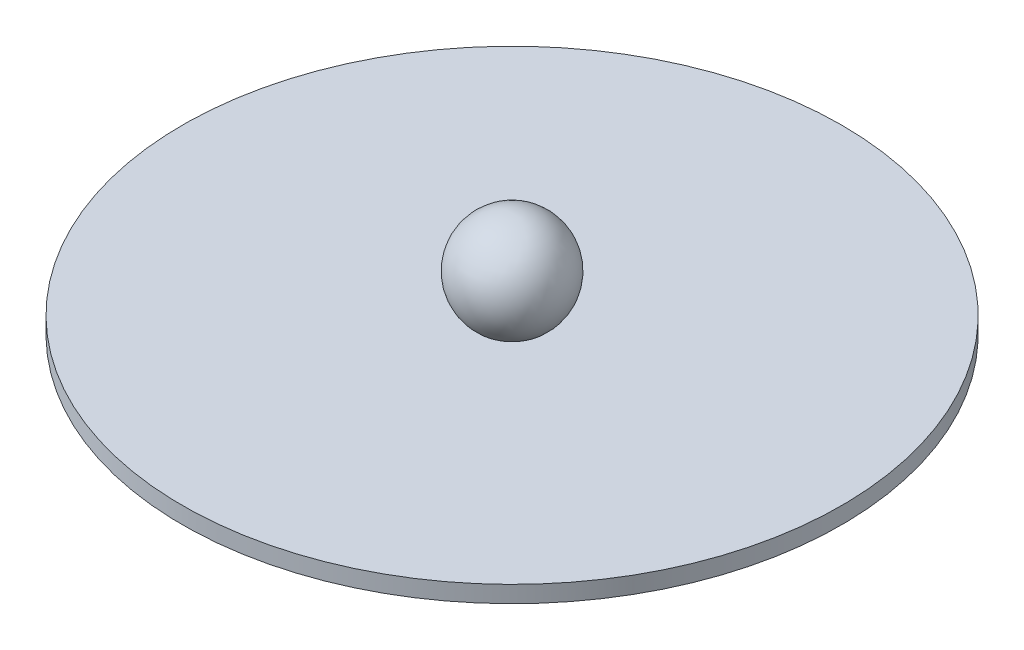
SolidWorks part; units mm, degrees
ref_plane "Front" through (0, 0, 0) normal (0, 0, 1) x (1, 0, 0)
ref_plane "Top" through (0, 0, 0) normal (0, 1, 0) x (1, 0, 0)
ref_plane "Right" through (0, 0, 0) normal (1, 0, 0) x (0, 0, -1)
sketch "Sketch1" plane through (0, 0, 0) normal (0, 0, 1) x (1, 0, 0)
  line L0 (0, 0) -> (0, 90.5826) construction
  line L1 (125.095, 12.7) -> (125.095, 6.35)
  line L2 (125.095, 6.35) -> (120.015, 6.35)
  line L3 (120.015, 6.35) -> (113.665, 0)
  line L4 (113.665, 0) -> (0, 0)
  line L5 (0, 0) -> (0, 12.7)
  line L6 (0, 12.7) -> (125.095, 12.7)
  dimension "D1" = 125.095
  dimension "D2" = 12.7
  dimension "D3" = 45
  dimension "D4" = 6.35
  dimension "D5" = 5.08
revolve "Revolve1" add sketch "Sketch1" angle 360 about L0
sketch "Sketch2" plane through (0, 0, 0) normal (0, 0, 1) x (1, 0, 0)
  line L0 (0, 0) -> (0, 27.2643) construction
  line L1 (0, 46.3143) -> (0, 8.2143)
  arc A0 (0, 8.2143) -> (0, 46.3143) centre (0, 27.2643) ccw
  dimension "D1" = 38.1
revolve "Revolve2" add sketch "Sketch2" angle 360 about L0
